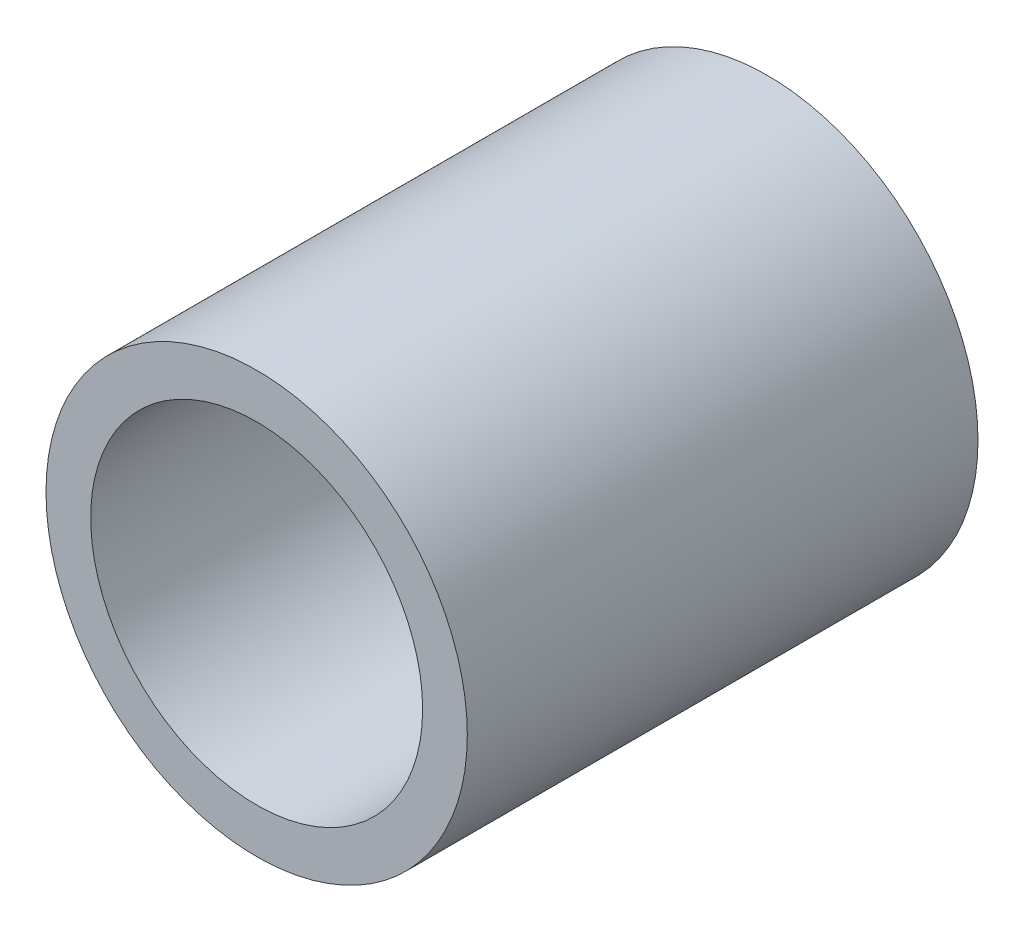
SolidWorks part; units mm, degrees
ref_plane "前视基准面" through (0, 0, 0) normal (0, 0, 1) x (1, 0, 0)
ref_plane "上视基准面" through (0, 0, 0) normal (0, 1, 0) x (1, 0, 0)
ref_plane "右视基准面" through (0, 0, 0) normal (1, 0, 0) x (0, 0, -1)
other "Configuration Table"
sketch "草图1" plane through (0, 0, 0) normal (0, 0, 1) x (1, 0, 0)
  circle A0 centre (0, 0) radius 2.6
  circle A1 centre (0, 0) radius 3.3
  dimension "D1" = 5.2
  dimension "D2" = 6.6
extrude "凸台-拉伸1" add sketch "草图1" along normal blind 8
